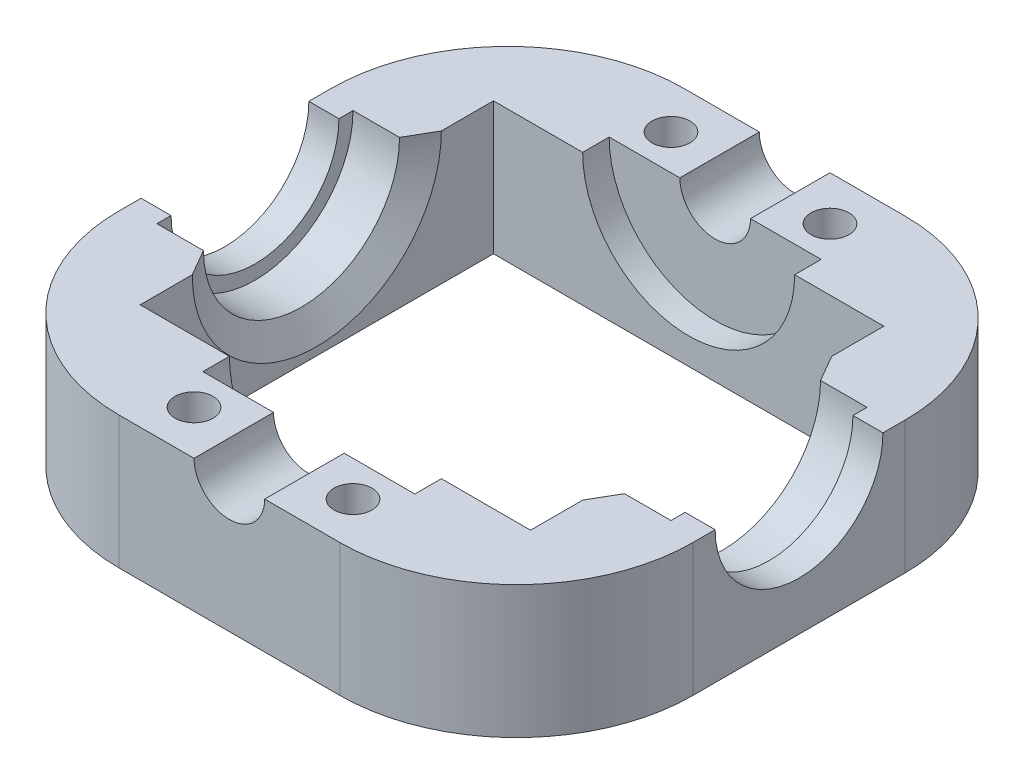
SolidWorks part; units mm, degrees
ref_plane "Спереди" through (0, 0, 0) normal (0, 0, 1) x (1, 0, 0)
ref_plane "Сверху" through (0, 0, 0) normal (0, 1, 0) x (1, 0, 0)
ref_plane "Справа" through (0, 0, 0) normal (1, 0, 0) x (0, 0, -1)
sketch "Sketch1" plane through (0, 0, 0) normal (0, 1, 0) x (1, 0, 0)
  line L1 (32.5, -32) -> (-32.5, -32)
  line L2 (32.5, -32) -> (32.5, 32)
  line L3 (32.5, 32) -> (-32.5, 32)
  line L4 (-32.5, -32) -> (-32.5, 32)
  line L5 (32.5, -32) -> (-32.5, 32) construction
  line L6 (32.5, 32) -> (-32.5, -32) construction
  line L7 (22.1, -20) -> (-22.1, -20)
  line L8 (22.1, -20) -> (22.1, 20)
  line L9 (22.1, 20) -> (-22.1, 20)
  line L10 (-22.1, -20) -> (-22.1, 20)
  line L11 (22.1, -20) -> (-22.1, 20) construction
  line L12 (22.1, 20) -> (-22.1, -20) construction
  point P0 (0, 0)
  point P6 (0, 0)
  dimension "D1" = 65
  dimension "D2" = 64
  dimension "D3" = 40
  dimension "D4" = 44.2
extrude "Boss-Extrude1" add sketch "Sketch1" along normal blind 15
sketch "Sketch3" plane through (0, 15, 0) normal (0, 1, 0) x (1, 0, 0)
  line L0 (-22.1, 0) -> (-32.5, 0) construction
  line L1 (-22.1, 20) -> (-22.1, -20) construction
  line L2 (-32.5, 32) -> (-32.5, -32) construction
  line L3 (22.1, 0) -> (32.5, 0) construction
  line L4 (22.1, -20) -> (22.1, 20) construction
  line L5 (32.5, -32) -> (32.5, 32) construction
  line L10 (22.1, -11.1) -> (29.1, -11.1)
  line L11 (22.1, -11.1) -> (22.1, 0)
  line L12 (22.1, 0) -> (29.1, 0)
  line L13 (29.1, -11.1) -> (29.1, 0)
  line L14 (22.1, -11.1) -> (29.1, 0) construction
  line L15 (22.1, 0) -> (29.1, -11.1) construction
  line L16 (-29.1, -11.1) -> (-22.1, -11.1)
  line L17 (-29.1, -11.1) -> (-29.1, 0)
  line L18 (-29.1, 0) -> (-22.1, 0)
  line L19 (-22.1, -11.1) -> (-22.1, 0)
  line L20 (-29.1, -11.1) -> (-22.1, 0) construction
  line L21 (-29.1, 0) -> (-22.1, -11.1) construction
  point P18 (25.6, -5.55)
  point P23 (-25.6, -5.55)
  dimension "D1" = 7
  dimension "D2" = 11.1
revolve "Cut-Revolve1" cut sketch "Sketch3" angle 360 about L12
sketch "Sketch4" plane through (32.5, 0, 0) normal (1, 0, 0) x (0, 0, -1)
  line L0 (-32, 15) -> (32, 15) construction
  circle A0 centre (0, 15) radius 9.5
  dimension "D1" = 19
extrude "Cut-Extrude2" cut sketch "Sketch4" against normal through all
sketch "Sketch5" plane through (0, 0, 32) normal (0, 0, 1) x (1, 0, 0)
  line L0 (-32.5, 15) -> (32.5, 15) construction
  circle A0 centre (0, 15) radius 4
  dimension "D1" = 8
extrude "Cut-Extrude3" cut sketch "Sketch5" against normal through all
sketch "Sketch8" plane through (0, 15, 0) normal (0, 1, 0) x (1, 0, 0)
  line L1 (-18, -16.5) -> (18, -16.5) construction
  line L2 (-18, -16.5) -> (-18, 16.5) construction
  line L3 (-18, 16.5) -> (18, 16.5) construction
  line L4 (18, -16.5) -> (18, 16.5) construction
  line L5 (-18, -16.5) -> (18, 16.5) construction
  line L6 (-18, 16.5) -> (18, -16.5) construction
  line L7 (-9, 27) -> (9, 27) construction
  line L8 (-9, 27) -> (-9, -27) construction
  line L9 (-9, -27) -> (9, -27) construction
  line L10 (9, 27) -> (9, -27) construction
  line L11 (-9, 27) -> (9, -27) construction
  line L12 (-9, -27) -> (9, 27) construction
  circle A0 centre (18, 16.5) radius 2.15
  circle A1 centre (18, -16.5) radius 2.15
  circle A2 centre (-18, -16.5) radius 2.15
  circle A3 centre (-18, 16.5) radius 2.15
  circle A4 centre (9, -27) radius 2.15
  circle A5 centre (-9, -27) radius 2.15
  circle A6 centre (-9, 27) radius 2.15
  circle A7 centre (9, 27) radius 2.15
  point P0 (0, 0)
  point P10 (0, 0)
  dimension "D3" = 4.3
  dimension "D1" = 33
  dimension "D2" = 36
  dimension "D4" = 18
  dimension "D5" = 54
extrude "Cut-Extrude6" cut sketch "Sketch8" against normal through all
fillet "Fillet1" radius 20 4 edges at (-32.5, 7.5, 32) (-32.5, 7.5, -32) (32.5, 7.5, -32) (32.5, 7.5, 32)
chamfer "Chamfer1" distance 3 angle 30 2 edges at (-22.1, 3.9, 0) (22.1, 3.9, 0)
sketch "Sketch9" plane through (0, 15, 0) normal (0, 1, 0) x (1, 0, 0)
  line L0 (0, 29.8714) -> (0, -31.0419) construction
  line L1 (-4, 20) -> (-22.1, 20) construction
  line L2 (-12, -23) -> (0, -23)
  line L3 (-12, -23) -> (-12, -20)
  line L4 (-12, -20) -> (0, -20)
  line L5 (0, -23) -> (0, -20)
  line L6 (-12, -23) -> (0, -20) construction
  line L7 (-12, -20) -> (0, -23) construction
  line L8 (-12, 20) -> (0, 20)
  line L9 (-12, 20) -> (-12, 23)
  line L10 (-12, 23) -> (0, 23)
  line L11 (0, 20) -> (0, 23)
  line L12 (-12, 20) -> (0, 23) construction
  line L13 (-12, 23) -> (0, 20) construction
  line L14 (-22.1, -20) -> (-4, -20) construction
  point P3 (-6, -21.5)
  point P8 (-6, 21.5)
  dimension "D1" = 3
  dimension "D2" = 12
revolve "Cut-Revolve2" cut sketch "Sketch9" angle 360 about L0
